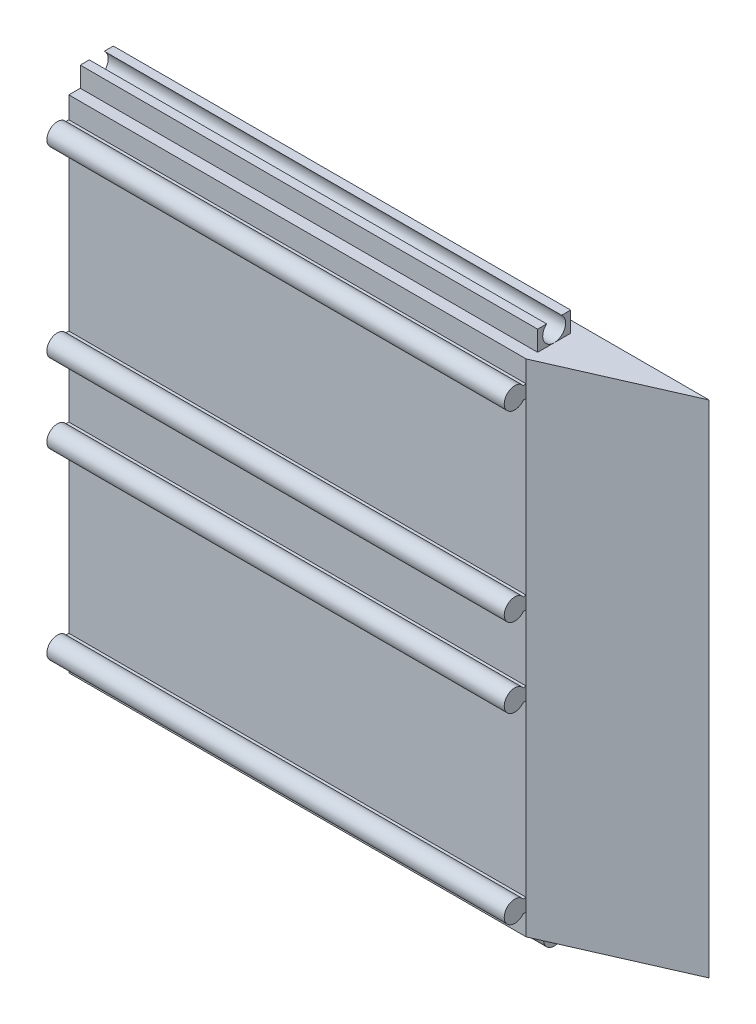
SolidWorks part; units mm, degrees
ref_plane "Спереди" through (0, 0, 0) normal (0, 0, 1) x (1, 0, 0)
ref_plane "Сверху" through (0, 0, 0) normal (0, 1, 0) x (1, 0, 0)
ref_plane "Справа" through (0, 0, 0) normal (1, 0, 0) x (0, 0, -1)
ref_plane "Плоскость4" through (90, 0, 0) normal (1, 0, 0) x (0, 0, -1)
sketch "Эскиз1" plane through (90, 0, 0) normal (1, 0, 0) x (0, 0, -1)
  line L0 (6.75, 40.9062) -> (6.75, 135.75)
  line L1 (6.75, 135.75) -> (-11.5938, 135.75)
  line L2 (-11.5938, 133.25) -> (-11, 133.25)
  line L3 (-11, 133.25) -> (-11, 99.75)
  line L4 (-11, 99.75) -> (-11.5938, 99.75)
  line L5 (-11.5938, 97.25) -> (-11, 97.25)
  line L6 (-11, 97.25) -> (-11, 84.25)
  line L7 (-11, 84.25) -> (-11.5938, 84.25)
  line L8 (-11.5938, 81.75) -> (-11, 81.75)
  line L9 (-11, 81.75) -> (-11, 48.25)
  line L10 (-11, 48.25) -> (-11.5938, 48.25)
  line L11 (-11.5938, 45.75) -> (-11, 45.75)
  line L12 (-11, 45.75) -> (-11, 41.5)
  line L13 (-11, 41.5) -> (-6.75, 41.5)
  line L14 (-6.75, 41.5) -> (-6.75, 40.9062)
  line L15 (-4.25, 40.9062) -> (-4.25, 41.5)
  line L16 (-4.25, 41.5) -> (4.25, 41.5)
  line L17 (4.25, 41.5) -> (4.25, 40.9062)
  arc A0 (-11.5938, 135.75) -> (-11.5938, 133.25) centre (-13.25, 134.5) ccw
  arc A1 (-11.5938, 99.75) -> (-11.5938, 97.25) centre (-13.25, 98.5) ccw
  arc A2 (-11.5938, 84.25) -> (-11.5938, 81.75) centre (-13.25, 83) ccw
  arc A3 (-11.5938, 48.25) -> (-11.5938, 45.75) centre (-13.25, 47) ccw
  arc A4 (-6.75, 40.9062) -> (-4.25, 40.9062) centre (-5.5, 39.25) ccw
  arc A5 (4.25, 40.9062) -> (6.75, 40.9062) centre (5.5, 39.25) ccw
extrude "Бобышка-Вытянуть1" add sketch "Эскиз1" against normal blind 90
sketch "Эскиз2" plane through (0, 135.75, 0) normal (0, 1, 0) x (-1, 0, 0)
  line L0 (-90, -6.75) -> (-90, 11)
  line L1 (-90, 11) -> (0, 11)
  line L2 (0, 11) -> (0, -6.75)
  line L3 (0, -6.75) -> (-90, -6.75)
extrude "Бобышка-Вытянуть2" add sketch "Эскиз2" along normal blind 8.2
sketch "Эскиз3" plane through (0, 0, -6.75) normal (0, 0, -1) x (-1, 0, 0)
  line L0 (-90, 41.5) -> (-90, 143.95)
  line L1 (-90, 143.95) -> (0, 143.95)
  line L2 (0, 143.95) -> (0, 41.5)
  line L3 (0, 41.5) -> (-90, 41.5)
extrude "Бобышка-Вытянуть3" add sketch "Эскиз3" along normal blind 8.2
sketch "Эскиз4" plane through (0, 0, 0) normal (-1, 0, 0) x (0, 0, 1)
  line L0 (-14.95, 41.5) -> (-11, 41.5)
  line L1 (-11, 41.5) -> (-11, 43.75)
  line L2 (-11, 43.75) -> (-14.95, 43.75)
  line L3 (-14.95, 43.75) -> (-14.95, 41.5)
extrude "Вырез-Вытянуть1" cut sketch "Эскиз4" against normal through all
sketch "Эскиз5" plane through (0, 0, 0) normal (-1, 0, 0) x (0, 0, 1)
  line L0 (-14.95, 50.25) -> (-11, 50.25)
  line L1 (-11, 50.25) -> (-11, 79.75)
  line L2 (-11, 79.75) -> (-14.95, 79.75)
  line L3 (-14.95, 79.75) -> (-14.95, 50.25)
extrude "Вырез-Вытянуть2" cut sketch "Эскиз5" against normal through all
sketch "Эскиз6" plane through (0, 0, 0) normal (-1, 0, 0) x (0, 0, 1)
  line L0 (-14.95, 86.25) -> (-11, 86.25)
  line L1 (-11, 86.25) -> (-11, 95.25)
  line L2 (-11, 95.25) -> (-14.95, 95.25)
  line L3 (-14.95, 95.25) -> (-14.95, 86.25)
extrude "Вырез-Вытянуть3" cut sketch "Эскиз6" against normal through all
sketch "Эскиз7" plane through (0, 0, 0) normal (-1, 0, 0) x (0, 0, 1)
  line L0 (-14.95, 101.75) -> (-11, 101.75)
  line L1 (-11, 101.75) -> (-11, 131.25)
  line L2 (-11, 131.25) -> (-14.95, 131.25)
  line L3 (-14.95, 131.25) -> (-14.95, 101.75)
extrude "Вырез-Вытянуть4" cut sketch "Эскиз7" against normal through all
sketch "Эскиз8" plane through (0, 0, 0) normal (-1, 0, 0) x (0, 0, 1)
  line L0 (-14.95, 143.95) -> (-14.95, 137.75)
  line L1 (-14.95, 137.75) -> (-11, 137.75)
  line L2 (-11, 137.75) -> (-11, 143.95)
  line L3 (-11, 143.95) -> (-14.95, 143.95)
extrude "Вырез-Вытянуть5" cut sketch "Эскиз8" against normal through all
sketch "Эскиз9" plane through (0, 0, 0) normal (-1, 0, 0) x (0, 0, 1)
  line L0 (-11, 143.95) -> (-11, 140)
  line L1 (-11, 140) -> (-8.75, 140)
  line L2 (-8.75, 140) -> (-8.75, 143.95)
  line L3 (-8.75, 143.95) -> (-11, 143.95)
extrude "Вырез-Вытянуть6" cut sketch "Эскиз9" against normal through all
sketch "Эскиз10" plane through (0, 0, 0) normal (-1, 0, 0) x (0, 0, 1)
  line L0 (-2.25, 143.95) -> (-2.25, 140)
  line L1 (-2.25, 140) -> (2.25, 140)
  line L2 (2.25, 140) -> (2.25, 143.95)
  line L3 (2.25, 143.95) -> (-2.25, 143.95)
extrude "Вырез-Вытянуть7" cut sketch "Эскиз10" against normal through all
sketch "Эскиз11" plane through (0, 0, 0) normal (-1, 0, 0) x (0, 0, 1)
  line L0 (11, 143.95) -> (8.75, 143.95)
  line L1 (8.75, 143.95) -> (8.75, 140)
  line L2 (8.75, 140) -> (11, 140)
  line L3 (11, 140) -> (11, 143.95)
extrude "Вырез-Вытянуть8" cut sketch "Эскиз11" against normal through all
sketch "Эскиз12" plane through (90, 0, 0) normal (1, 0, 0) x (0, 0, -1)
  line L0 (10.1, 139.1) -> (-10.1, 139.1)
  line L1 (-10.1, 139.1) -> (-10.1, 42.4)
  line L2 (-10.1, 42.4) -> (10.1, 42.4)
  line L3 (10.1, 42.4) -> (10.1, 139.1)
extrude "Вырез-Вытянуть9" cut sketch "Эскиз12" against normal blind 86
hole_wizard "Диаметр отверстия Ø8.3 (8.3)1" positions "Эскиз14" profile "Эскиз13" hole size "Ø8.3" standard "Ansi Metric"
sketch "Эскиз14" plane through (0, 0, 0) normal (-1, 0, 0) x (0, 0, 1)
  point P0 (0, 90)
sketch "Эскиз13" plane through (0, 90, 0) normal (0, 1, 0) x (0, 0, 1)
  line L0 (0, 0) -> (0, 3.2)
  line L1 (0, 3.2) -> (4.15, 3.2)
  line L2 (4.15, 3.2) -> (4.15, 0)
  line L5 (4.15, 0) -> (0, 0)
  line L10 (0, 3.2) -> (-4.15, 3.2) construction
  line L11 (0, -6.35) -> (0, 107.95) construction
  dimension "Диаметр отверстия" = 8.3
  dimension "Глубина отверстия" = 3.2
  dimension "Угол заточки сверла" = 180
hole_wizard "Диаметр отверстия Ø4.5 (4.5)1" positions "Эскиз16" profile "Эскиз15" hole size "Ø4.5" standard "Ansi Metric"
sketch "Эскиз16" plane through (0, 0, 0) normal (-1, 0, 0) x (0, 0, 1)
  point P0 (-13.25, 47)
  point P1 (-13.25, 83)
  point P2 (-13.25, 98.5)
  point P3 (-13.25, 134.5)
  point P4 (-5.5, 142.25)
  point P5 (5.5, 142.25)
sketch "Эскиз15" plane through (0, 47, -13.25) normal (0, 1, 0) x (0, 0, 1)
  line L0 (0, 0) -> (0, 90)
  line L1 (0, 90) -> (2.25, 90)
  line L2 (2.25, 90) -> (2.25, 0)
  line L5 (2.25, 0) -> (0, 0)
  line L11 (0, -6.35) -> (0, 107.95) construction
  dimension "Диаметр сквозного отверстия" = 4.5
  dimension "Глубина сквозного отверстия" = 90
hole_wizard "Диаметр отверстия Ø2.5 (2.5)1" positions "Эскиз18" profile "Эскиз17" hole size "Ø2.5" standard "Ansi Metric"
sketch "Эскиз18" plane through (90, 0, 0) normal (1, 0, 0) x (0, 0, -1)
  point P0 (-13.25, 98.5)
  point P1 (-13.25, 134.5)
  point P2 (-13.25, 47)
  point P3 (-13.25, 83)
  point P4 (5.5, 39.25)
  point P5 (-5.5, 39.25)
sketch "Эскиз17" plane through (90, 98.5, 13.25) normal (0, 1, 0) x (0, 0, -1)
  line L0 (0, 0) -> (0, 90)
  line L1 (0, 90) -> (1.25, 90)
  line L2 (1.25, 90) -> (1.25, 0)
  line L5 (1.25, 0) -> (0, 0)
  line L11 (0, -6.35) -> (0, 107.95) construction
  dimension "Диаметр сквозного отверстия" = 2.5
  dimension "Глубина сквозного отверстия" = 90
sketch "Эскиз19" plane through (0, 0, 0) normal (-1, 0, 0) x (0, 0, 1)
  circle A0 centre (0, 90) radius 4.5031
extrude "Бобышка-Вытянуть4" add sketch "Эскиз19" against normal blind 3
sketch "Эскиз20" plane through (90, 0, 0) normal (1, 0, 0) x (0, 0, -1)
  circle A0 centre (-13.25, 134.5) radius 1.6499
  circle A1 centre (-13.25, 98.5) radius 1.6606
  circle A2 centre (-13.25, 83) radius 1.4307
  circle A3 centre (-13.25, 47) radius 1.5733
  circle A4 centre (-5.5, 39.25) radius 1.502
  circle A5 centre (5.5, 39.25) radius 1.538
extrude "Бобышка-Вытянуть5" add sketch "Эскиз20" against normal blind 90
sketch "Эскиз21" plane through (4, 0, 0) normal (1, 0, 0) x (0, 0, -1)
  line L0 (-4.25, 41.5) -> (4.25, 41.5) construction
  line L1 (2.25, 140) -> (-2.25, 140) construction
  line L2 (0, 140) -> (0, 41.5)
  line L3 (0, 140) -> (0, 145.9579)
  line L4 (0, 41.5) -> (0, 35.6143)
  line L5 (0, 35.6143) -> (18.7474, 35.6143)
  line L6 (18.7474, 35.6143) -> (18.7474, 145.9579)
  line L7 (18.7474, 145.9579) -> (0, 145.9579)
  point P0 (0, 41.5)
  point P1 (0, 140)
  point P4 (-26.3091, 154.161)
extrude "Вырез-Вытянуть10" cut sketch "Эскиз21" along normal blind 112 and the other way blind 112
sketch "Эскиз22" plane through (4, 0, 0) normal (1, 0, 0) x (0, 0, -1)
  line L4 (0, 42.4) -> (0, 139.1)
  line L5 (0, 139.1) -> (-10.1, 139.1)
  line L6 (-10.1, 139.1) -> (-10.1, 42.4)
  line L7 (-10.1, 42.4) -> (0, 42.4)
  line L8 (0, 42.4) -> (0, 139.1)
  line L9 (0, 139.1) -> (-10.1, 139.1)
  line L10 (-10.1, 139.1) -> (-10.1, 42.4)
  line L11 (-10.1, 42.4) -> (0, 42.4)
  dimension "D1" = 0
extrude "Бобышка-Вытянуть6" add sketch "Эскиз22" along normal blind 20 and the other way blind 3
sketch "Эскиз23" plane through (0, 139.1, 0) normal (0, -1, 0) x (1, 0, 0)
  line L4 (90, 10.1) -> (24, 10.1)
  line L5 (24, 10.1) -> (24, 0)
  line L6 (24, 0) -> (90, 0)
  line L7 (90, 0) -> (90, 10.1)
  line L8 (90, 10.1) -> (24, 10.1)
  line L9 (24, 10.1) -> (24, 0)
  line L10 (24, 0) -> (90, 0)
  line L11 (90, 0) -> (90, 10.1)
  dimension "D1" = 0
extrude "Бобышка-Вытянуть7" add sketch "Эскиз23" along normal blind 10
sketch "Эскиз24" plane through (0, 42.4, 0) normal (0, 1, 0) x (1, 0, 0)
  line L4 (90, 0) -> (24, 0)
  line L5 (24, 0) -> (24, -10.1)
  line L6 (24, -10.1) -> (90, -10.1)
  line L7 (90, -10.1) -> (90, 0)
  line L8 (90, 0) -> (24, 0)
  line L9 (24, 0) -> (24, -10.1)
  line L10 (24, -10.1) -> (90, -10.1)
  line L11 (90, -10.1) -> (90, 0)
  dimension "D1" = 0
extrude "Бобышка-Вытянуть8" add sketch "Эскиз24" along normal blind 10
sketch "Эскиз25" plane through (90, 0, 0) normal (1, 0, 0) x (0, 0, -1)
  line L4 (-10.1, 52.4) -> (0, 52.4)
  line L5 (0, 52.4) -> (0, 129.1)
  line L6 (0, 129.1) -> (-10.1, 129.1)
  line L7 (-10.1, 129.1) -> (-10.1, 52.4)
  line L8 (-10.1, 52.4) -> (0, 52.4)
  line L9 (0, 52.4) -> (0, 129.1)
  line L10 (0, 129.1) -> (-10.1, 129.1)
  line L11 (-10.1, 129.1) -> (-10.1, 52.4)
  dimension "D1" = 0
extrude "Бобышка-Вытянуть9" add sketch "Эскиз25" against normal blind 20
sketch "Эскиз26" plane through (90, 0, 0) normal (1, 0, 0) x (0, 0, -1)
  line L0 (-11, 140) -> (0, 140)
  line L1 (0, 140) -> (0, 41.5)
  line L2 (0, 41.5) -> (-11, 41.5)
  line L3 (-11, 41.5) -> (-11, 140)
extrude "Бобышка-Вытянуть10" add sketch "Эскиз26" along normal blind 25
sketch "Эскиз27" plane through (0, 41.5, 0) normal (0, -1, 0) x (1, 0, 0)
  line L0 (90, 11) -> (115, 0)
  line L1 (90, -55) -> (90, 55) construction
  line L2 (0, 11) -> (90, 11) construction
  line L6 (115, 11) -> (115, 0) construction
  line L7 (0, 11) -> (115, 11) construction
  line L8 (115, 11) -> (115, 0)
  line L9 (90, 11) -> (115, 11)
extrude "Вырез-Вытянуть13" cut sketch "Эскиз27" against normal blind 123
sketch "Эскиз29" plane through (0, 129.1, 0) normal (0, -1, 0) x (1, 0, 0)
  line L4 (24, 0) -> (70, 0)
  line L5 (70, 0) -> (70, 10.1)
  line L6 (70, 10.1) -> (24, 10.1)
  line L7 (24, 10.1) -> (24, 0)
  line L8 (24, 0) -> (70, 0)
  line L9 (70, 0) -> (70, 10.1)
  line L10 (70, 10.1) -> (24, 10.1)
  line L11 (24, 10.1) -> (24, 0)
  dimension "D1" = 0
extrude "Бобышка-Вытянуть11" add sketch "Эскиз29" along normal blind 78 and the other way blind 2
